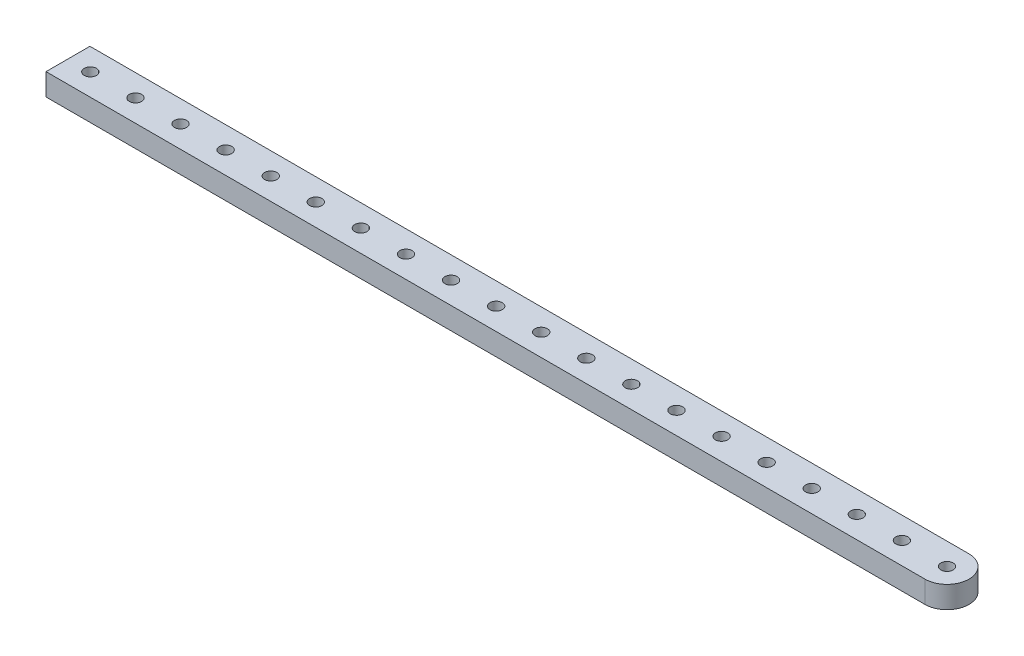
SolidWorks part; units mm, degrees
ref_plane "Front Plane" through (0, 0, 0) normal (0, 0, 1) x (1, 0, 0)
ref_plane "Top Plane" through (0, 0, 0) normal (0, 1, 0) x (1, 0, 0)
ref_plane "Right Plane" through (0, 0, 0) normal (1, 0, 0) x (0, 0, -1)
ref_plane "Plane1" through (0, 6.35, 0) normal (0, 1, 0) x (1, 0, 0)
sketch "Sketch1" plane through (0, 6.35, 0) normal (0, 1, 0) x (1, 0, 0)
  line L0 (130.3867, 6.35) -> (-130.3867, 6.35)
  line L1 (-130.3867, -6.35) -> (130.3867, -6.35)
  arc A0 (130.3867, -6.35) -> (130.3867, 6.35) centre (130.3867, 0) ccw
  arc A1 (-130.3867, 6.35) -> (-130.3867, -6.35) centre (-130.3867, 0) ccw
  circle A2 centre (130.3867, 0) radius 1.778
  circle A3 centre (117.348, 0) radius 1.778
  circle A4 centre (104.3093, 0) radius 1.778
  circle A5 centre (91.2707, 0) radius 1.778
  circle A6 centre (78.232, 0) radius 1.778
  circle A7 centre (65.1933, 0) radius 1.778
  circle A8 centre (52.1547, 0) radius 1.778
  circle A9 centre (39.116, 0) radius 1.778
  circle A10 centre (26.0773, 0) radius 1.778
  circle A11 centre (13.0387, 0) radius 1.778
  circle A12 centre (0, 0) radius 1.778
  circle A13 centre (-13.0387, 0) radius 1.778
  circle A14 centre (-26.0773, 0) radius 1.778
  circle A15 centre (-39.116, 0) radius 1.778
  circle A16 centre (-52.1547, 0) radius 1.778
  circle A17 centre (-65.1933, 0) radius 1.778
  circle A18 centre (-78.232, 0) radius 1.778
  circle A19 centre (-91.2707, 0) radius 1.778
  circle A20 centre (-104.3093, 0) radius 1.778
  circle A21 centre (-117.348, 0) radius 1.778
  circle A22 centre (-130.3867, 0) radius 1.778
  dimension "D2" = 3.556
  dimension "D1" = 12.7
extrude "Boss-Extrude1" add sketch "Sketch1" against normal blind 6.35
sketch "Sketch2" plane through (0, 6.35, 0) normal (0, 1, 0) x (1, 0, 0)
  line L1 (-143.2999, 6.9145) -> (-123.8246, 6.9145)
  line L2 (-143.2999, 6.9145) -> (-143.2999, -9.6103)
  line L3 (-143.2999, -9.6103) -> (-123.8246, -9.6103)
  line L4 (-123.8246, 6.9145) -> (-123.8246, -9.6103)
extrude "Cut-Extrude1" cut sketch "Sketch2" against normal blind 10.16
